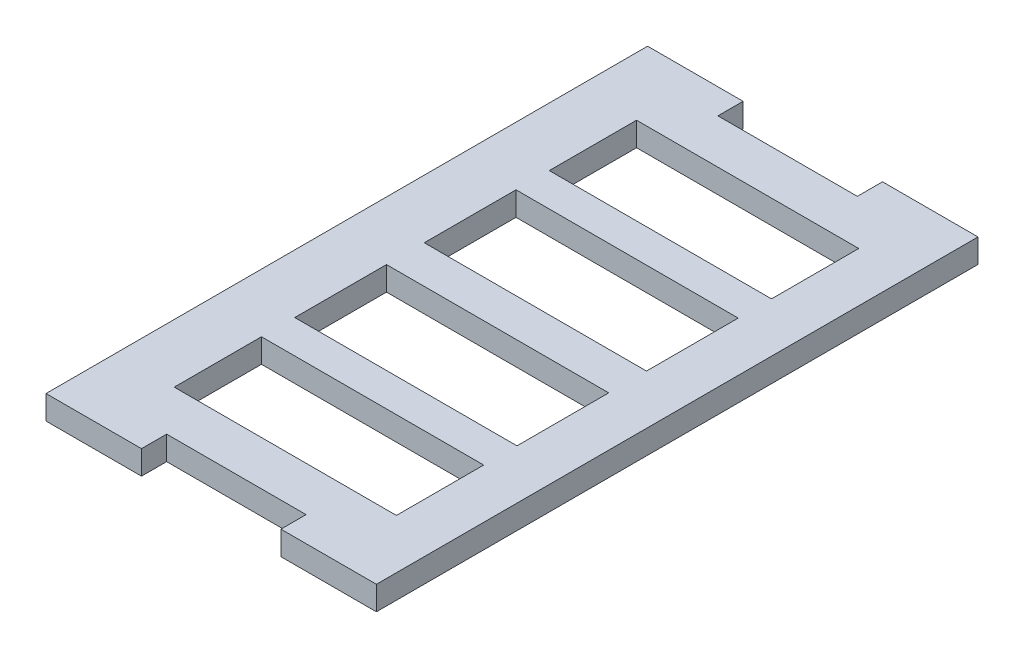
SolidWorks part; units mm, degrees
ref_plane "Front Plane" through (0, 0, 0) normal (0, 0, 1) x (1, 0, 0)
ref_plane "Top Plane" through (0, 0, 0) normal (0, 1, 0) x (1, 0, 0)
ref_plane "Right Plane" through (0, 0, 0) normal (1, 0, 0) x (0, 0, -1)
sketch "Sketch1" plane through (0, 0, 0) normal (0, 1, 0) x (1, 0, 0)
  line L0 (-0.1788, 25.704) -> (-0.1788, 46.434) construction
  line L1 (-14.7788, 25.1624) -> (14.4212, 25.1624)
  line L2 (-34.7788, 25.4332) -> (-34.7788, -90.5668)
  line L3 (-14.7788, -90.296) -> (14.4212, -90.296)
  line L4 (34.4212, 25.4332) -> (34.4212, -90.5668)
  line L6 (-34.7788, 25.4332) -> (-34.7788, 30.4332)
  line L7 (-34.7788, 30.4332) -> (-14.7788, 30.4332)
  line L8 (-14.7788, 25.1624) -> (-14.7788, 30.4332)
  line L9 (-34.7788, -32.5668) -> (34.4212, -32.5668) construction
  line L10 (14.4212, 25.1624) -> (14.4212, 30.4332)
  line L11 (34.4212, 25.4332) -> (34.4212, 30.4332)
  line L12 (34.4212, 30.4332) -> (14.4212, 30.4332)
  line L13 (34.4212, -90.5668) -> (34.4212, -95.5668)
  line L14 (34.4212, -95.5668) -> (14.4212, -95.5668)
  line L15 (14.4212, -90.296) -> (14.4212, -95.5668)
  line L16 (-14.7788, -90.296) -> (-14.7788, -95.5668)
  line L17 (-34.7788, -95.5668) -> (-14.7788, -95.5668)
  line L18 (-34.7788, -90.5668) -> (-34.7788, -95.5668)
  line L25 (24.0308, -55.7349) -> (24.0308, -36.5236)
  line L26 (-22.5089, 15.8496) -> (24.0308, 15.8496)
  line L27 (-22.5089, 15.8496) -> (-22.5089, -2.4271)
  line L28 (-22.5089, -2.4271) -> (24.0308, -2.4271)
  line L29 (24.0308, 15.8496) -> (24.0308, -2.4271)
  line L30 (-22.5089, -9.3986) -> (24.0308, -9.3986)
  line L31 (-22.5089, -9.3986) -> (-22.5089, -28.61)
  line L32 (-22.5089, -28.61) -> (24.0308, -28.61)
  line L33 (24.0308, -9.3986) -> (24.0308, -28.61)
  line L34 (-22.5089, -36.5236) -> (24.0308, -36.5236)
  line L35 (-22.5089, -55.7349) -> (-22.5089, -36.5236)
  line L36 (-22.5089, -55.7349) -> (24.0308, -55.7349)
  line L37 (24.0308, -80.9832) -> (24.0308, -62.7065)
  line L38 (-22.5089, -62.7065) -> (24.0308, -62.7065)
  line L39 (-22.5089, -80.9832) -> (-22.5089, -62.7065)
  line L40 (-22.5089, -80.9832) -> (24.0308, -80.9832)
  dimension "D1" = 69.2
  dimension "D2" = 116
  dimension "D3" = 20
  dimension "D4" = 5
extrude "Boss-Extrude1" add sketch "Sketch1" along normal blind 5
